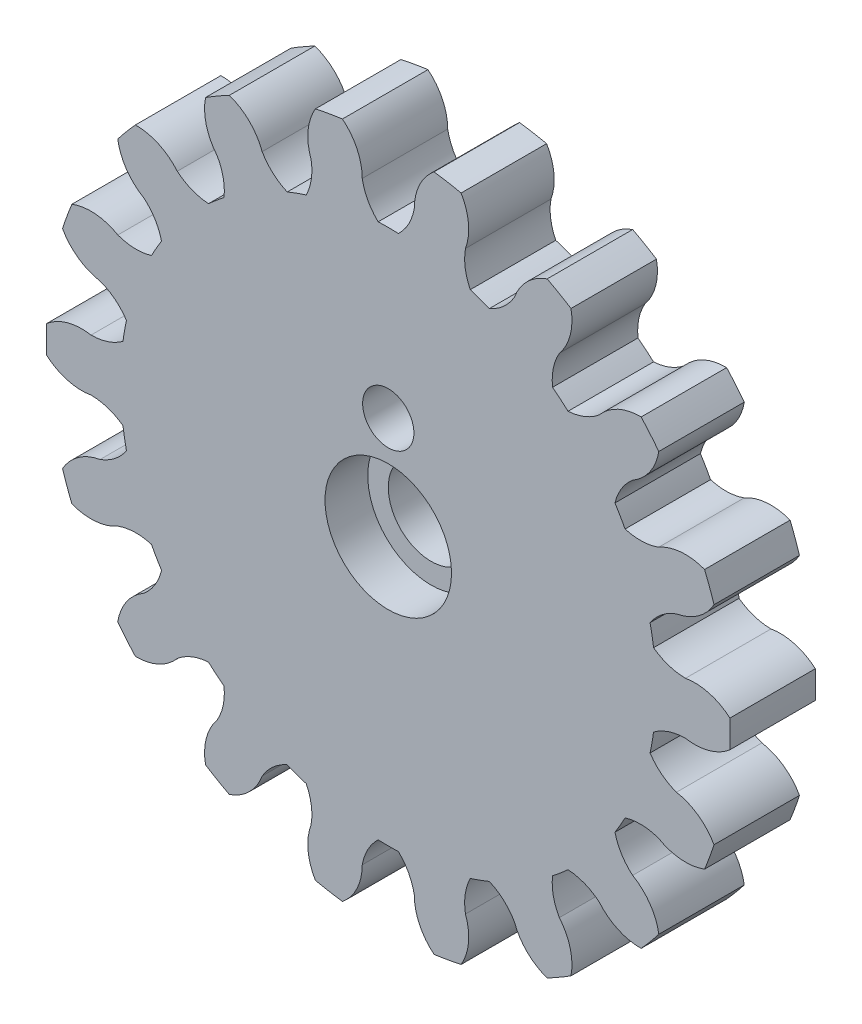
SolidWorks part; units mm, degrees
ref_plane "Alzado" through (0, 0, 0) normal (0, 0, 1) x (1, 0, 0)
ref_plane "Planta" through (0, 0, 0) normal (0, 1, 0) x (1, 0, 0)
ref_plane "Vista lateral" through (0, 0, 0) normal (1, 0, 0) x (0, 0, -1)
sketch "Croquis1" plane through (0, 0, 0) normal (0, 0, 1) x (1, 0, 0)
  circle A0 centre (0, 0) radius 20
  circle A1 centre (0, 0) radius 2.5
  circle A2 centre (0, 6) radius 1.5
  dimension "D1" = 40
  dimension "D2" = 5
  dimension "D4" = 3
  dimension "D3" = 6
extrude "Saliente-Extruir1" add sketch "Croquis1" along normal blind 5
sketch "Croquis2" plane through (0, 0, 5) normal (0, 0, 1) x (1, 0, 0)
  line L0 (0, 0) -> (0, 21.6776) construction
  arc A0 (2.6786, 19.8198) -> (-2.6786, 19.8198) centre (0, 0) ccw
  arc A1 (0.5915, 15.6538) -> (-0.5915, 15.6538) centre (0, 0) ccw
  arc A2 (1.57, 17.9314) -> (-1.57, 17.9314) centre (0, 0) ccw construction
  arc A3 (-1.5222, 17.3857) -> (-2.6786, 19.8198) centre (-4.6622, 17.3857) ccw
  arc A5 (-1.5222, 17.3857) -> (-0.5915, 15.6538) centre (1.57, 17.9314) ccw
  arc A6 (2.6786, 19.8198) -> (1.5222, 17.3857) centre (4.6622, 17.3857) ccw
  arc A7 (0.5915, 15.6538) -> (1.5222, 17.3857) centre (-1.57, 17.9314) ccw
  dimension "D1" = 31.33
  dimension "D2" = 36
  dimension "D3" = 6.28
  dimension "D4" = 1.57
extrude "Cortar-Extruir1" cut sketch "Croquis2" against normal through all
pattern_circular "MatrizC1" count 18 over 360 about axis through (0, 0, 0) along (0, 0, 1) of "Cortar-Extruir1"
sketch "Croquis3" plane through (0, 0, 5) normal (0, 0, 1) x (1, 0, 0)
  circle A0 centre (0, 0) radius 3.7
  dimension "D1" = 7.4
extrude "Cortar-Extruir2" cut sketch "Croquis3" against normal blind 2.5
sketch "Croquis4" plane through (0, 0, 0) normal (0, 0, -1) x (-1, 0, 0)
  circle A0 centre (0, 6) radius 2.25
  dimension "D1" = 4.5
extrude "Cortar-Extruir3" cut sketch "Croquis4" against normal blind 2.5
